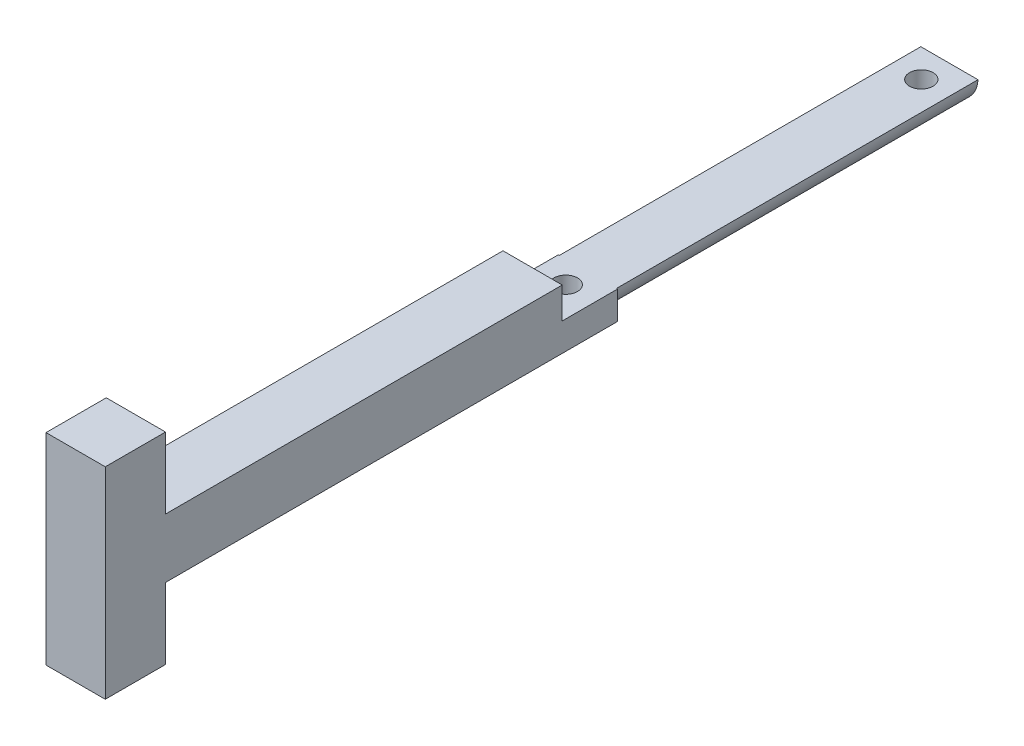
SolidWorks part; units mm, degrees
ref_plane "정면" through (0, 0, 0) normal (0, 0, 1) x (1, 0, 0)
ref_plane "윗면" through (0, 0, 0) normal (0, 1, 0) x (1, 0, 0)
ref_plane "우측면" through (0, 0, 0) normal (1, 0, 0) x (0, 0, -1)
sketch "스케치1" plane through (0, 0, 0) normal (0, 0, 1) x (1, 0, 0)
  circle A0 centre (0, 0) radius 2.85
  dimension "D1" = 5.7
extrude "보스-돌출1" add sketch "스케치1" along normal blind 31 contours A0
sketch "스케치3" plane through (0, 0, 0) normal (0, 0, -1) x (-1, 0, 0)
  line L1 (2.95, -2.95) -> (-2.95, -2.95)
  line L2 (2.95, -2.95) -> (2.95, 2.95)
  line L3 (2.95, 2.95) -> (-2.95, 2.95)
  line L4 (-2.95, -2.95) -> (-2.95, 2.95)
  line L5 (2.95, -2.95) -> (-2.95, 2.95) construction
  line L6 (2.95, 2.95) -> (-2.95, -2.95) construction
  point P0 (0, 0)
  dimension "D1" = 5.9
  dimension "D2" = 5.9
extrude "보스-돌출2" add sketch "스케치3" along normal blind 5
sketch "스케치4" plane through (0, 0, -5) normal (0, 0, -1) x (-1, 0, 0)
  circle A0 centre (0, 0) radius 5
  dimension "D1" = 10
extrude "보스-돌출3" add sketch "스케치4" along normal blind 7
sketch "스케치6" plane through (0, 0, -12) normal (0, 0, -1) x (-1, 0, 0)
  circle A0 centre (0, 0) radius 11.5
  dimension "D1" = 23
extrude "보스-돌출4" add sketch "스케치6" along normal blind 2
sketch "스케치8" plane through (0, 0, -14) normal (0, 0, -1) x (-1, 0, 0)
  circle A0 centre (0, 0) radius 4.5
  dimension "D1" = 9
extrude "컷-돌출2" cut sketch "스케치8" against normal blind 7.5
sketch "스케치9" plane through (0, 0, -14) normal (0, 0, -1) x (-1, 0, 0)
  line L0 (0, 0) -> (0, 14.2749) construction
  line L1 (0, 0) -> (-5.348, 12.9112) construction
  circle A0 centre (3.4442, 8.3149) radius 1.25
  circle A1 centre (-3.4442, 8.3149) radius 1.25
  circle A2 centre (8.3149, 3.4442) radius 1.25
  circle A3 centre (8.3149, -3.4442) radius 1.25
  circle A4 centre (3.4442, -8.3149) radius 1.25
  circle A5 centre (-3.4442, -8.3149) radius 1.25
  circle A6 centre (-8.3149, -3.4442) radius 1.25
  circle A7 centre (-8.3149, 3.4442) radius 1.25
  point P24 (0, 0)
  dimension "D2" = 8
  dimension "D4" = 2.5
  dimension "D1" = 22.5
  dimension "D3" = 9
extrude "컷-돌출3" cut sketch "스케치9" against normal blind 5.5
sketch "스케치10" plane through (0, 2.95, 0) normal (0, 1, 0) x (1, 0, 0)
  circle A0 centre (0, 2.2) radius 1.175
  dimension "D2" = 2.35
  dimension "D1" = 2.2
extrude "컷-돌출7" cut sketch "스케치10" against normal blind 10
sketch "스케치11" plane through (0, 2.95, 0) normal (0, 1, 0) x (1, 0, 0)
  line L2 (-2.95, 5) -> (-2.95, 0) construction
  line L4 (-2.95, 2.6468) -> (2.95, 2.6468) construction
  line L5 (2.95, 5) -> (2.95, 0) construction
sketch "스케치12" plane through (0, 0, 31) normal (0, 0, 1) x (1, 0, 0)
  line L0 (-2.95, 2.95) -> (2.95, 2.95) construction
  line L1 (2.95, -2.95) -> (-2.95, -2.95)
  line L2 (2.95, -2.95) -> (2.95, 2.95)
  line L3 (2.95, 2.95) -> (-2.95, 2.95)
  line L4 (-2.95, -2.95) -> (-2.95, 2.95)
  line L5 (2.95, -2.95) -> (-2.95, 2.95) construction
  line L6 (2.95, 2.95) -> (-2.95, -2.95) construction
  line L7 (-2.95, -2.95) -> (-2.95, 2.95) construction
  point P0 (0, 0)
extrude "보스-돌출5" add sketch "스케치12" along normal blind 45
sketch "스케치15" plane through (0, 0, 76) normal (0, 0, 1) x (1, 0, 0)
  line L1 (2.95, -10.0246) -> (-2.95, -10.0246)
  line L2 (2.95, -10.0246) -> (2.95, 10.0246)
  line L3 (2.95, 10.0246) -> (-2.95, 10.0246)
  line L4 (-2.95, -10.0246) -> (-2.95, 10.0246)
  line L5 (2.95, -10.0246) -> (-2.95, 10.0246) construction
  line L6 (2.95, 10.0246) -> (-2.95, -10.0246) construction
  point P0 (0, 0)
  dimension "D1" = 5.9
extrude "보스-돌출6" add sketch "스케치15" along normal blind 6
sketch "스케치7" plane through (0, 0, -14) normal (0, 0, -1) x (-1, 0, 0)
  circle A0 centre (0, 12) radius 1.05
  dimension "D1" = 2.1
  dimension "D2" = 12
sketch "스케치16" plane through (0, 2.95, 0) normal (0, 1, 0) x (1, 0, 0)
  line L0 (2.95, -31) -> (-2.95, -31) construction
  circle A0 centre (0, -33.2) radius 1.175
  dimension "D2" = 2.35
  dimension "D1" = 2.2
extrude "컷-돌출8" cut sketch "스케치16" against normal blind 10
sketch "스케치21" plane through (2.95, 0, 0) normal (1, 0, 0) x (0, 0, -1)
  line L1 (5, 2.95) -> (-36.5, 2.95)
  line L2 (5, 2.95) -> (5, -0.15)
  line L3 (5, -0.15) -> (-36.5, -0.15)
  line L4 (-36.5, 2.95) -> (-36.5, -0.15)
  dimension "D1" = 41.5
  dimension "D2" = 3.1
extrude "컷-돌출9" cut sketch "스케치21" against normal blind 10
sketch "스케치22" plane through (0, 0, 0) normal (0, 0, 1) x (1, 0, 0)
  circle A0 centre (0, 0) radius 2.85
  dimension "D1" = 5.7
extrude "컷-돌출10" cut sketch "스케치22" against normal blind 5 flip side to cut
sketch "스케치23" plane through (0, 0, -14) normal (0, 0, -1) x (-1, 0, 0)
  circle A0 centre (0, 0) radius 14.4116
extrude "컷-돌출11" cut sketch "스케치23" against normal blind 9
